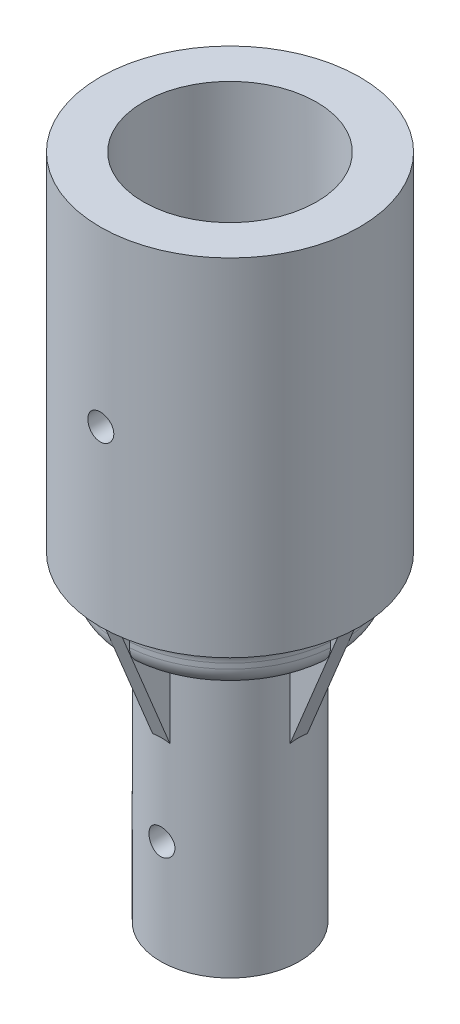
SolidWorks part; units mm, degrees
ref_plane "Front Plane" through (0, 0, 0) normal (0, 0, 1) x (1, 0, 0)
ref_plane "Top Plane" through (0, 0, 0) normal (0, 1, 0) x (1, 0, 0)
ref_plane "Right Plane" through (0, 0, 0) normal (1, 0, 0) x (0, 0, -1)
sketch "Sketch1" plane through (0, 0, 0) normal (0, 1, 0) x (1, 0, 0)
  circle A0 centre (0, 0) radius 4
  circle A1 centre (0, 0) radius 8
  dimension "D1" = 8
  dimension "D2" = 4
extrude "Boss-Extrude1" add sketch "Sketch1" along normal blind 32
sketch "Sketch2" plane through (0, 32, 0) normal (0, 1, 0) x (1, 0, 0)
  circle A0 centre (0, 0) radius 12.654
extrude "Boss-Extrude2" add sketch "Sketch2" along normal blind 5
sketch "Sketch3" plane through (0, 37, 0) normal (0, 1, 0) x (1, 0, 0)
  circle A0 centre (0, 0) radius 15
  circle A1 centre (0, 0) radius 10
  dimension "D1" = 5
  dimension "D2" = 20
extrude "Boss-Extrude3" add sketch "Sketch3" along normal blind 40
fillet "Fillet1" radius 2.2 3 edges at (0, 32, 12.654) (0, 32, 8) (0, 37, 12.654)
sketch "Sketch4" plane through (0, 0, 0) normal (0, 0, 1) x (1, 0, 0)
  line L0 (-15, 37) -> (15, 37) construction
  circle A0 centre (0, 57) radius 1.5
  circle A1 centre (0, 12) radius 1.5
  point P7 (0, 0)
  point P8 (0, 0)
  dimension "D1" = 3
  dimension "D2" = 3
  dimension "D3" = 20
  dimension "D4" = 12
extrude "Cut-Extrude1" cut sketch "Sketch4" against normal mid plane 40
sketch "Sketch5" plane through (0, 0, 0) normal (0, 0, 1) x (1, 0, 0)
  line L0 (14, 37) -> (7, 20)
  line L2 (-14.854, 37) -> (14.854, 37) construction
  point P3 (6.6818, 19.9565)
  point P4 (0, 0)
  point P5 (0, 0)
  point P9 (0, 0)
  point P10 (12.0093, 37)
  dimension "D1" = 20
  dimension "D2" = 7
  dimension "D3" = 14
rib "Rib5" sketch "Sketch5" sketch "Sketch5" thickness 2 extrusion direction parallel to sketch draft on no parameters "D1"=2
pattern_circular "CirPattern1" count 4 over 360 about axis through (0, 0, 0) along (0, 1, 0) of "Rib5"
